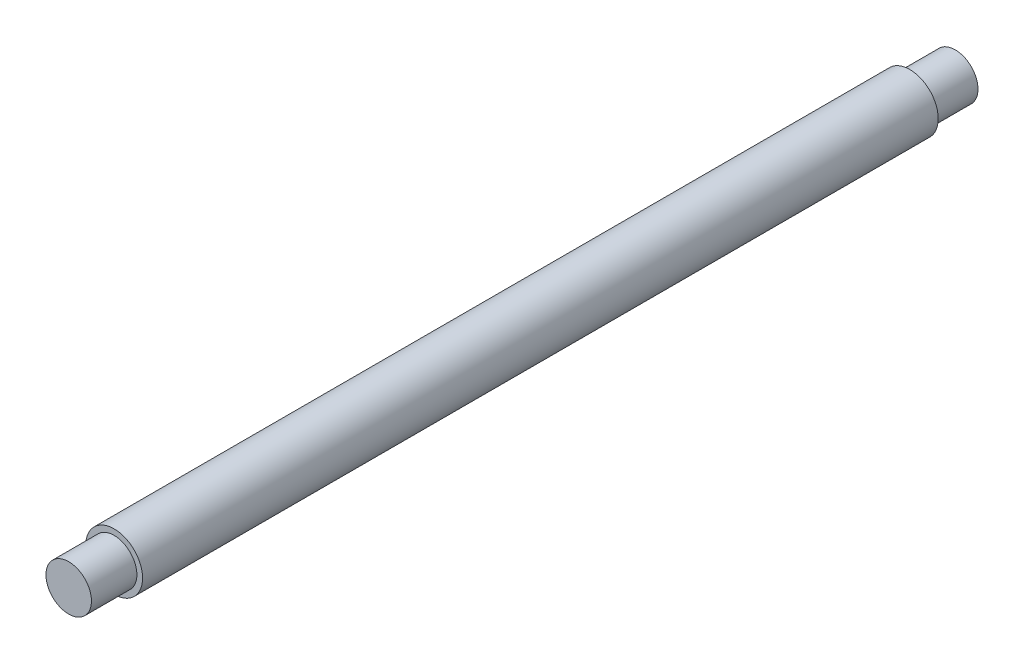
SolidWorks part; units mm, degrees
ref_plane "Front Plane" through (0, 0, 0) normal (0, 0, 1) x (1, 0, 0)
ref_plane "Top Plane" through (0, 0, 0) normal (0, 1, 0) x (1, 0, 0)
ref_plane "Right Plane" through (0, 0, 0) normal (1, 0, 0) x (0, 0, -1)
sketch "Sketch1" plane through (0, 0, 0) normal (0, 0, 1) x (1, 0, 0)
  circle A0 centre (0, 0) radius 5
  dimension "D1" = 10
extrude "Boss-Extrude1" add sketch "Sketch1" along normal mid plane 140
sketch "Sketch2" plane through (0, 0, 70) normal (0, 0, 1) x (1, 0, 0)
  circle A0 centre (0, 0) radius 4
  dimension "D1" = 8
extrude "Boss-Extrude2" add sketch "Sketch2" along normal blind 8
mirror "Mirror1" about plane through (0, 0, 0) normal (0, 0, 1) of "Boss-Extrude2"
